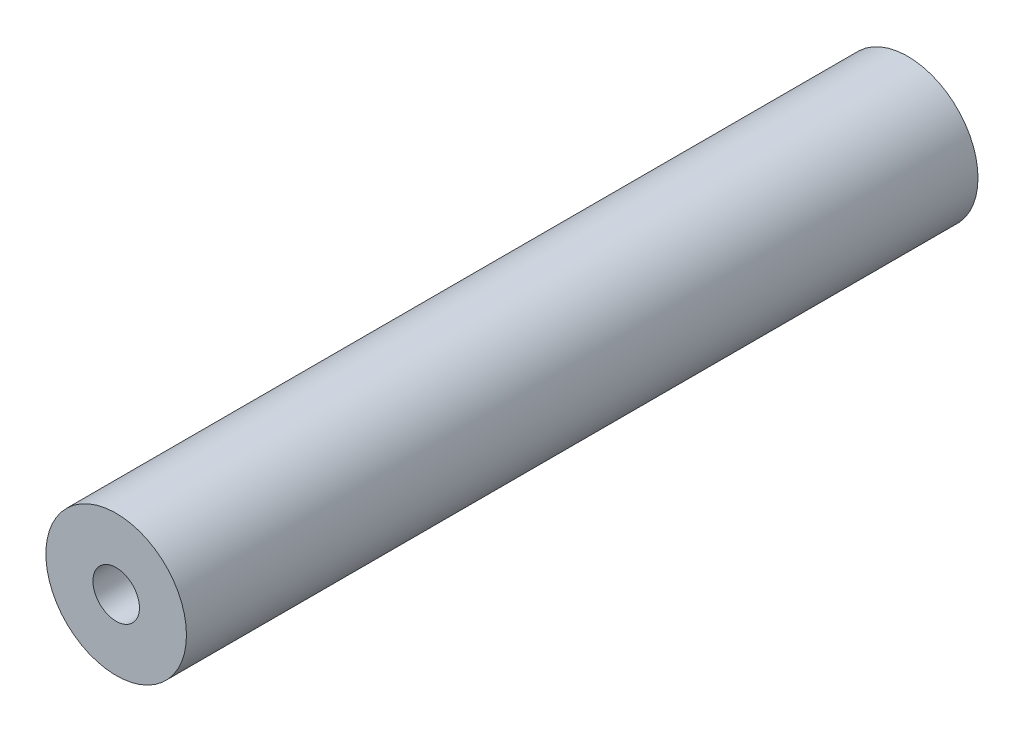
SolidWorks part; units mm, degrees
ref_plane "Front Plane" through (0, 0, 0) normal (0, 0, 1) x (1, 0, 0)
ref_plane "Top Plane" through (0, 0, 0) normal (0, 1, 0) x (1, 0, 0)
ref_plane "Right Plane" through (0, 0, 0) normal (1, 0, 0) x (0, 0, -1)
sketch "Sketch1" plane through (0, 0, 0) normal (0, 0, 1) x (1, 0, 0)
  circle A0 centre (0, 0) radius 6.35
  dimension "D1" = 12.7
extrude "Boss-Extrude1" add sketch "Sketch1" against normal blind 71.5
sketch "Sketch2" plane through (0, 0, 0) normal (0, 0, 1) x (1, 0, 0)
  circle A0 centre (0, 0) radius 2.1
  dimension "D1" = 4.2
extrude "Cut-Extrude1" cut sketch "Sketch2" against normal blind 15
